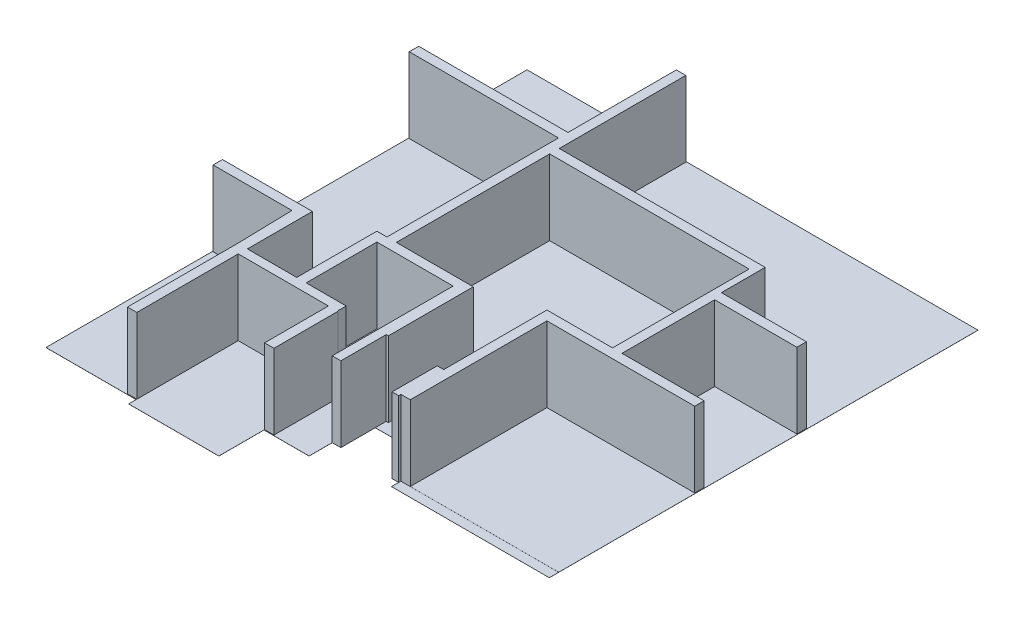
SolidWorks part; units mm, degrees
ref_plane "Front Plane" through (0, 0, 0) normal (0, 0, 1) x (1, 0, 0)
ref_plane "Top Plane" through (0, 0, 0) normal (0, 1, 0) x (1, 0, 0)
ref_plane "Right Plane" through (0, 0, 0) normal (1, 0, 0) x (0, 0, -1)
sketch "Sketch1" plane through (0, 0, 0) normal (0, 1, 0) x (1, 0, 0)
  line L0 (3657.6, 0) -> (3657.6, -304.8)
  line L1 (0, 0) -> (3657.6, 0)
  line L2 (0, 0) -> (0, 19507.2)
  line L3 (0, 19507.2) -> (18288, 19507.2)
  line L4 (18288, 0) -> (18288, 19507.2)
  line L5 (0, 0) -> (18288, 19507.2) construction
  line L6 (0, 19507.2) -> (18288, 0) construction
  line L7 (3657.6, -304.8) -> (7315.2, -304.8)
  line L8 (7315.2, -304.8) -> (7315.2, 0)
  line L9 (7315.2, 0) -> (7315.2, 1524)
  line L10 (7315.2, 1524) -> (9144, 1524)
  line L11 (9144, 1524) -> (9144, 2413)
  line L12 (9144, 2413) -> (11887.2, 2413)
  line L13 (11887.2, 2413) -> (11887.2, 0)
  line L14 (11887.2, 0) -> (18288, 0)
  point P4 (9144, 9753.6)
  dimension "D1" = 18288
  dimension "D2" = 19507.2
  dimension "D3" = 7315.2
  dimension "D4" = 1524
  dimension "D5" = 304.8
  dimension "D6" = 1828.8
  dimension "D7" = 889
  dimension "D8" = 3657.6
  dimension "D9" = 2743.2
  dimension "D10" = 2413
extrude "Boss-Extrude1" add sketch "Sketch1" along normal blind 2.54
sketch "Sketch2" plane through (0, 2.54, 0) normal (0, 1, 0) x (1, 0, 0)
  line L0 (6079.1869, 13964.5874) -> (6079.1869, 19507.2)
  line L11 (18288, 19507.2) -> (0, 19507.2) construction
  line L14 (6079.1869, 13964.5874) -> (14548.139, 13964.5874)
  line L15 (14548.139, 13964.5874) -> (14548.139, 12187.8841)
  line L16 (14548.139, 12187.8841) -> (18288, 12187.8841)
  line L17 (18288, 0) -> (18288, 19507.2) construction
  line L24 (6464.1393, 19507.2) -> (6464.1393, 14349.5397)
  line L25 (6464.1393, 14349.5397) -> (14814.6445, 14349.5397)
  line L26 (14814.6445, 14349.5397) -> (14814.6445, 12572.8365)
  line L27 (14814.6445, 12572.8365) -> (18288, 12572.8365)
  line L28 (6079.1869, 19507.2) -> (6464.1393, 19507.2)
  line L29 (18288, 12572.8365) -> (18288, 12187.8841)
  dimension "D1" = 5542.6126
  dimension "D2" = 5157.6603
  dimension "D3" = 8468.9521
  dimension "D4" = 8350.5052
  dimension "D5" = 1776.7032
  dimension "D6" = 3473.3555
  dimension "D7" = 1776.7032
  dimension "D8" = 3739.861
extrude "Boss-Extrude2" add sketch "Sketch2" along normal blind 3048
sketch "Sketch3" plane through (0, 2.54, 0) normal (0, 1, 0) x (1, 0, 0)
  line L0 (0, 19507.2) -> (0, 0) construction
  line L1 (0, 14704.8804) -> (6079.1869, 14704.8804)
  line L2 (0, 14704.8804) -> (0, 15089.8328)
  line L3 (0, 15089.8328) -> (6079.1869, 15089.8328)
  line L4 (6079.1869, 14704.8804) -> (6079.1869, 15089.8328)
  line L5 (0, 14704.8804) -> (6079.1869, 15089.8328) construction
  line L6 (0, 15089.8328) -> (6079.1869, 14704.8804) construction
  line L7 (6079.1869, 19507.2) -> (6079.1869, 13964.5874) construction
  line L8 (6079.1869, 19507.2) -> (0, 19507.2) construction
  point P4 (3039.5935, 14897.3566)
  dimension "D1" = 384.9524
  dimension "D2" = 4417.3672
extrude "Boss-Extrude3" add sketch "Sketch3" along normal blind 3048
sketch "Sketch4" plane through (0, 2.54, 0) normal (0, 1, 0) x (1, 0, 0)
  line L0 (18288, 0) -> (18288, 12187.8841) construction
  line L1 (11887.2, 2413) -> (11887.2, 0) construction
  line L2 (18288, 2122.5591) -> (11887.2, 2122.5591)
  line L3 (18288, 2122.5591) -> (18288, 2503.5591)
  line L4 (18288, 2503.5591) -> (11887.2, 2503.5591)
  line L5 (11887.2, 2122.5591) -> (11887.2, 2503.5591)
  line L6 (18288, 2122.5591) -> (11887.2, 2503.5591) construction
  line L7 (18288, 2503.5591) -> (11887.2, 2122.5591) construction
  line L8 (11887.2, 0) -> (18288, 0) construction
  point P6 (15087.6, 2313.0591)
  dimension "D1" = 381
  dimension "D2" = 2122.5591
extrude "Boss-Extrude4" add sketch "Sketch4" along normal blind 3048
sketch "Sketch5" plane through (0, 2.54, 0) normal (0, 1, 0) x (1, 0, 0)
  line L1 (9144, 2413) -> (9579.2092, 2413)
  line L2 (9144, 2413) -> (9144, 7747)
  line L3 (9144, 7747) -> (9579.2092, 7747)
  line L4 (9579.2092, 2413) -> (9579.2092, 7747)
  line L5 (9144, 2413) -> (9579.2092, 7747) construction
  line L6 (9144, 7747) -> (9579.2092, 2413) construction
  point P5 (9361.6046, 5080)
  dimension "D1" = 435.2092
  dimension "D2" = 5334
extrude "Boss-Extrude5" add sketch "Sketch5" along normal blind 3048
sketch "Sketch6" plane through (0, 2.54, 0) normal (0, 1, 0) x (1, 0, 0)
  line L0 (18288, 2503.5591) -> (11887.2, 2503.5591) construction
  line L1 (12268.2, 2503.5591) -> (11887.2, 2503.5591)
  line L2 (12268.2, 2503.5591) -> (12268.2, 8426.1696)
  line L3 (12268.2, 8426.1696) -> (11887.2, 8426.1696)
  line L4 (11887.2, 2503.5591) -> (11887.2, 8426.1696)
  line L5 (12268.2, 2503.5591) -> (11887.2, 8426.1696) construction
  line L6 (12268.2, 8426.1696) -> (11887.2, 2503.5591) construction
  line L7 (11887.2, 2122.5591) -> (11887.2, 0) construction
  point P5 (12077.7, 5464.8644)
  dimension "D1" = 381
extrude "Boss-Extrude7" add sketch "Sketch6" along normal blind 3048
sketch "Sketch7" plane through (0, 2.54, 0) normal (0, 1, 0) x (1, 0, 0)
  line L0 (18288, 2503.5591) -> (18288, 12187.8841) construction
  line L1 (12268.2, 8426.1696) -> (18288, 8426.1696)
  line L2 (12268.2, 8426.1696) -> (12268.2, 8045.1696)
  line L3 (12268.2, 8045.1696) -> (18288, 8045.1696)
  line L4 (18288, 8426.1696) -> (18288, 8045.1696)
  line L5 (12268.2, 8426.1696) -> (18288, 8045.1696) construction
  line L6 (12268.2, 8045.1696) -> (18288, 8426.1696) construction
  point P4 (15278.1, 8235.6696)
  dimension "D1" = 381
extrude "Boss-Extrude8" add sketch "Sketch7" along normal blind 3048
sketch "Sketch8" plane through (0, 2.54, 0) normal (0, 1, 0) x (1, 0, 0)
  line L1 (7315.2, 1524) -> (7696.2, 1524)
  line L2 (7315.2, 1524) -> (7315.2, 4137.7312)
  line L3 (7315.2, 4137.7312) -> (7696.2, 4137.7312)
  line L4 (7696.2, 1524) -> (7696.2, 4137.7312)
  line L5 (7315.2, 1524) -> (7696.2, 4137.7312) construction
  line L6 (7315.2, 4137.7312) -> (7696.2, 1524) construction
  point P4 (7505.7, 2830.8656)
  dimension "D1" = 381
extrude "Boss-Extrude9" add sketch "Sketch8" along normal blind 3048
sketch "Sketch9" plane through (0, 2.54, 0) normal (0, 1, 0) x (1, 0, 0)
  line L1 (3657.6, 0) -> (3276.6, 0)
  line L2 (3657.6, 0) -> (3657.6, 4182.505)
  line L3 (3657.6, 4182.505) -> (3276.6, 4182.505)
  line L4 (3276.6, 0) -> (3276.6, 4182.505)
  line L5 (3657.6, 0) -> (3276.6, 4182.505) construction
  line L6 (3657.6, 4182.505) -> (3276.6, 0) construction
  point P4 (3467.1, 2091.2525)
  dimension "D1" = 381
extrude "Boss-Extrude10" add sketch "Sketch9" along normal blind 3048
sketch "Sketch10" plane through (0, 2.54, 0) normal (0, 1, 0) x (1, 0, 0)
  line L0 (7696.2, 4137.7312) -> (7315.2, 4137.7312) construction
  line L1 (7674.1926, 4137.7312) -> (3668.37, 4137.7312)
  line L2 (7674.1926, 4137.7312) -> (7674.1926, 4497.6301)
  line L3 (7674.1926, 4497.6301) -> (3668.37, 4497.6301)
  line L4 (3668.37, 4137.7312) -> (3668.37, 4497.6301)
  line L5 (7674.1926, 4137.7312) -> (3668.37, 4497.6301) construction
  line L6 (7674.1926, 4497.6301) -> (3668.37, 4137.7312) construction
  point P4 (5671.2813, 4317.6806)
extrude "Boss-Extrude11" add sketch "Sketch10" along normal blind 3048
sketch "Sketch11" plane through (0, 2.54, 0) normal (0, 1, 0) x (1, 0, 0)
  line L0 (3276.6, 4182.505) -> (3276.6, 4499.7193)
  line L1 (3276.6, 4182.505) -> (3276.6, 0) construction
  line L2 (3276.6, 4182.505) -> (3276.6, 0) construction
  line L3 (3276.6, 4499.7193) -> (3668.37, 4497.6301)
  line L4 (3668.37, 4497.6301) -> (3668.37, 4137.7312)
  line L5 (3668.37, 4137.7312) -> (3657.6, 4137.7312)
  line L6 (3657.6, 0) -> (3657.6, 4182.505) construction
  line L7 (3657.6, 4137.7312) -> (3657.6, 4182.505)
  line L8 (3657.6, 4182.505) -> (3276.6, 4182.505) construction
  line L9 (3657.6, 4182.505) -> (3276.6, 4182.505) construction
  line L10 (3657.6, 4182.505) -> (3276.6, 4182.505)
extrude "Boss-Extrude12" add sketch "Sketch11" along normal blind 3048
sketch "Sketch13" plane through (0, 2.54, 0) normal (0, 1, 0) x (1, 0, 0)
  line L0 (9144, 7747) -> (5671.2813, 7747)
  line L1 (5671.2813, 7747) -> (5671.2813, 4497.6301)
  line L2 (7674.1926, 4497.6301) -> (3668.37, 4497.6301) construction
  line L3 (5671.2813, 4497.6301) -> (6052.2813, 4497.6301)
  line L4 (7674.1926, 4497.6301) -> (3668.37, 4497.6301) construction
  line L5 (6052.2813, 4497.6301) -> (6052.2813, 7366)
  line L6 (6052.2813, 7366) -> (9144, 7366)
  line L7 (9144, 7747) -> (9144, 2413) construction
  line L8 (9144, 7366) -> (9144, 7747)
  dimension "D1" = 381
  dimension "D2" = 381
extrude "Boss-Extrude13" add sketch "Sketch13" along normal blind 3048
sketch "Sketch14" plane through (0, 2.54, 0) normal (0, 1, 0) x (1, 0, 0)
  line L0 (9579.2092, 7747) -> (5671.2813, 7747) construction
  line L1 (6079.1869, 13964.5874) -> (6460.1869, 13964.5874)
  line L2 (6079.1869, 13964.5874) -> (6079.1869, 7747)
  line L3 (6079.1869, 7747) -> (6460.1869, 7747)
  line L4 (6460.1869, 13964.5874) -> (6460.1869, 7747)
  line L5 (6079.1869, 13964.5874) -> (6460.1869, 7747) construction
  line L6 (6079.1869, 7747) -> (6460.1869, 13964.5874) construction
  point P4 (6269.6869, 10855.7937)
  dimension "D1" = 381
extrude "Boss-Extrude15" add sketch "Sketch14" along normal blind 3048
sketch "Sketch16" plane through (0, 2.54, 0) normal (0, 1, 0) x (1, 0, 0)
  line L1 (11887.2, 0) -> (18288, 0)
  line L2 (11887.2, 0) -> (11887.2, 2122.5591)
  line L3 (11887.2, 2122.5591) -> (18288, 2122.5591)
  line L4 (18288, 0) -> (18288, 2122.5591)
  line L5 (11887.2, 0) -> (18288, 2122.5591) construction
  line L6 (11887.2, 2122.5591) -> (18288, 0) construction
  point P5 (15087.6, 1061.2796)
extrude "Cut-Extrude2" cut sketch "Sketch16" against normal blind 3048
sketch "Sketch18" plane through (0, 2.54, 0) normal (0, 1, 0) x (1, 0, 0)
  line L0 (18288, 8426.1696) -> (11887.2, 8426.1696) construction
  line L1 (14548.139, 12187.8841) -> (14929.139, 12187.8841)
  line L2 (14548.139, 12187.8841) -> (14548.139, 8426.1696)
  line L3 (14548.139, 8426.1696) -> (14929.139, 8426.1696)
  line L4 (14929.139, 12187.8841) -> (14929.139, 8426.1696)
  line L5 (14548.139, 12187.8841) -> (14929.139, 8426.1696) construction
  line L6 (14548.139, 8426.1696) -> (14929.139, 12187.8841) construction
  point P4 (14738.639, 10307.0269)
  dimension "D1" = 381
extrude "Boss-Extrude16" add sketch "Sketch18" along normal blind 3048
sketch "Sketch19" plane through (0, 2.54, 0) normal (0, 1, 0) x (1, 0, 0)
  line L0 (3276.6, 4499.7193) -> (3668.37, 4497.6301)
  line L1 (3668.37, 4497.6301) -> (3276.6, 4499.7193) construction
  line L2 (5671.2813, 4497.6301) -> (3668.37, 4497.6301) construction
  line L3 (3668.37, 4497.6301) -> (3668.37, 7132.8491)
  line L4 (3668.37, 7132.8491) -> (0, 7132.8491)
  line L5 (0, 14704.8804) -> (0, 0) construction
  line L6 (0, 7132.8491) -> (0, 6751.8491)
  line L7 (0, 6751.8491) -> (3221.6739, 6751.8491)
  line L8 (3221.6739, 6751.8491) -> (3276.6, 4499.7193)
  dimension "D1" = 381
extrude "Boss-Extrude17" add sketch "Sketch19" along normal blind 3048
sketch "Sketch20" plane through (0, 0, 0) normal (0, 0, 1) x (1, 0, 0)
  line L1 (3276.6, 3050.54) -> (3657.6, 3050.54)
  line L2 (3276.6, 3050.54) -> (3276.6, 2.54)
  line L3 (3276.6, 2.54) -> (3657.6, 2.54)
  line L4 (3657.6, 3050.54) -> (3657.6, 2.54)
  line L5 (3276.6, 3050.54) -> (3657.6, 2.54) construction
  line L6 (3276.6, 2.54) -> (3657.6, 3050.54) construction
  point P4 (3467.1, 1526.54)
extrude "Cut-Extrude3" cut sketch "Sketch20" against normal blind 25.4
sketch "Sketch21" plane through (0, 0, -1524) normal (0, 0, 1) x (1, 0, 0)
  line L1 (7696.2, 2.54) -> (7315.2, 2.54)
  line L2 (7696.2, 2.54) -> (7696.2, 3050.54)
  line L3 (7696.2, 3050.54) -> (7315.2, 3050.54)
  line L4 (7315.2, 2.54) -> (7315.2, 3050.54)
  line L5 (7696.2, 2.54) -> (7315.2, 3050.54) construction
  line L6 (7696.2, 3050.54) -> (7315.2, 2.54) construction
  point P4 (7505.7, 1526.54)
extrude "Cut-Extrude4" cut sketch "Sketch21" against normal blind 25.4
sketch "Sketch22" plane through (0, 0, -2413) normal (0, 0, 1) x (1, 0, 0)
  line L1 (9579.2092, 2.54) -> (11887.2, 2.54)
  line L2 (9579.2092, 2.54) -> (9579.2092, 3050.54)
  line L3 (9579.2092, 3050.54) -> (11887.2, 3050.54)
  line L4 (11887.2, 2.54) -> (11887.2, 3050.54)
  line L5 (9579.2092, 2.54) -> (11887.2, 3050.54) construction
  line L6 (9579.2092, 3050.54) -> (11887.2, 2.54) construction
  point P4 (10733.2046, 1526.54)
extrude "Boss-Extrude18" add sketch "Sketch22" against normal blind 1828.8
sketch "Sketch23" plane through (0, 0, -2413) normal (0, 0, 1) x (1, 0, 0)
  line L0 (9144, 0) -> (11887.2, 0) construction
  line L1 (9492.1389, 0) -> (11624.0435, 0)
  line L2 (9492.1389, 0) -> (9492.1389, 3050.54)
  line L3 (9492.1389, 3050.54) -> (11624.0435, 3050.54)
  line L4 (11624.0435, 0) -> (11624.0435, 3050.54)
  line L5 (9492.1389, 0) -> (11624.0435, 3050.54) construction
  line L6 (9492.1389, 3050.54) -> (11624.0435, 0) construction
  line L7 (9144, 3050.54) -> (11887.2, 3050.54) construction
  point P4 (10558.0912, 1525.27)
extrude "Cut-Extrude5" cut sketch "Sketch23" against normal blind 1447.8
sketch "Sketch24" plane through (0, 0, -2413) normal (0, 0, 1) x (1, 0, 0)
  line L1 (9492.1389, 0) -> (9144, 0)
  line L2 (9492.1389, 0) -> (9492.1389, 3050.54)
  line L3 (9492.1389, 3050.54) -> (9144, 3050.54)
  line L4 (9144, 0) -> (9144, 3050.54)
  line L5 (9492.1389, 0) -> (9144, 3050.54) construction
  line L6 (9492.1389, 3050.54) -> (9144, 0) construction
  point P4 (9318.0694, 1525.27)
extrude "Cut-Extrude6" cut sketch "Sketch24" against normal blind 50.8
sketch "Sketch26" plane through (0, 0, -3860.8) normal (0, 0, 1) x (1, 0, 0)
  line L0 (9492.1389, 3050.54) -> (9492.1389, 0) construction
  line L1 (11624.0435, 3050.54) -> (9492.1389, 3050.54)
  line L2 (11624.0435, 3050.54) -> (11624.0435, 2.54)
  line L3 (11624.0435, 2.54) -> (9492.1389, 2.54)
  line L4 (9492.1389, 3050.54) -> (9492.1389, 2.54)
  line L5 (11624.0435, 3050.54) -> (9492.1389, 2.54) construction
  line L6 (11624.0435, 2.54) -> (9492.1389, 3050.54) construction
  line L7 (9492.1389, 0) -> (11624.0435, 0) construction
  point P4 (10558.0912, 1526.54)
  dimension "D1" = 2.54
extrude "Cut-Extrude7" cut sketch "Sketch26" against normal blind 441.706
sketch "Sketch28" plane through (0, 0, -2122.5591) normal (0, 0, 1) x (1, 0, 0)
  line L0 (18288, 3050.54) -> (18288, 0) construction
  line L1 (11887.2, 3050.54) -> (18288, 3050.54)
  line L2 (11887.2, 3050.54) -> (11887.2, 0.254)
  line L3 (11887.2, 0.254) -> (18288, 0.254)
  line L4 (18288, 3050.54) -> (18288, 0.254)
  line L5 (11887.2, 3050.54) -> (18288, 0.254) construction
  line L6 (11887.2, 0.254) -> (18288, 3050.54) construction
  line L7 (11887.2, 0) -> (18288, 0) construction
  point P4 (15087.6, 1525.397)
  dimension "D1" = 0.254
extrude "Cut-Extrude9" cut sketch "Sketch28" against normal blind 381
sketch "Sketch29" plane through (0, 0, 0) normal (-1, 0, 0) x (0, 0, 1)
  line L0 (-14704.8804, 3050.54) -> (-14704.8804, 2.54) construction
  line L1 (-15089.8328, 3050.54) -> (-14704.8804, 3050.54)
  line L2 (-15089.8328, 3050.54) -> (-15089.8328, 0.254)
  line L3 (-15089.8328, 0.254) -> (-14704.8804, 0.254)
  line L4 (-14704.8804, 3050.54) -> (-14704.8804, 0.254)
  line L5 (-15089.8328, 3050.54) -> (-14704.8804, 0.254) construction
  line L6 (-15089.8328, 0.254) -> (-14704.8804, 3050.54) construction
  line L7 (-19507.2, 0) -> (0, 0) construction
  point P4 (-14897.3566, 1525.397)
  dimension "D1" = 0.254
extrude "Cut-Extrude10" cut sketch "Sketch29" against normal blind 25.4
sketch "Sketch30" plane through (0, 0, 0) normal (-1, 0, 0) x (0, 0, 1)
  line L0 (-6751.8491, 3050.54) -> (-6751.8491, 2.54) construction
  line L1 (-7132.8491, 3050.54) -> (-6751.8491, 3050.54)
  line L2 (-7132.8491, 3050.54) -> (-7132.8491, 0.254)
  line L3 (-7132.8491, 0.254) -> (-6751.8491, 0.254)
  line L4 (-6751.8491, 3050.54) -> (-6751.8491, 0.254)
  line L5 (-7132.8491, 3050.54) -> (-6751.8491, 0.254) construction
  line L6 (-7132.8491, 0.254) -> (-6751.8491, 3050.54) construction
  line L7 (-19507.2, 0) -> (0, 0) construction
  point P4 (-6942.3491, 1525.397)
  dimension "D1" = 0.254
extrude "Cut-Extrude11" cut sketch "Sketch30" against normal blind 25.4
sketch "Sketch31" plane through (18288, 0, 0) normal (1, 0, 0) x (0, 0, -1)
  line L0 (8426.1696, 3050.54) -> (8426.1696, 2.54) construction
  line L1 (8045.1696, 3050.54) -> (8426.1696, 3050.54)
  line L2 (8045.1696, 3050.54) -> (8045.1696, 0.254)
  line L3 (8045.1696, 0.254) -> (8426.1696, 0.254)
  line L4 (8426.1696, 3050.54) -> (8426.1696, 0.254)
  line L5 (8045.1696, 3050.54) -> (8426.1696, 0.254) construction
  line L6 (8045.1696, 0.254) -> (8426.1696, 3050.54) construction
  line L7 (2122.5591, 0) -> (19507.2, 0) construction
  point P4 (8235.6696, 1525.397)
  dimension "D1" = 0.254
extrude "Cut-Extrude12" cut sketch "Sketch31" against normal blind 25.4
sketch "Sketch32" plane through (18288, 0, 0) normal (1, 0, 0) x (0, 0, -1)
  line L0 (12572.8365, 3050.54) -> (12572.8365, 2.54) construction
  line L1 (12187.8841, 3050.54) -> (12572.8365, 3050.54)
  line L2 (12187.8841, 3050.54) -> (12187.8841, 0.254)
  line L3 (12187.8841, 0.254) -> (12572.8365, 0.254)
  line L4 (12572.8365, 3050.54) -> (12572.8365, 0.254)
  line L5 (12187.8841, 3050.54) -> (12572.8365, 0.254) construction
  line L6 (12187.8841, 0.254) -> (12572.8365, 3050.54) construction
  line L7 (2122.5591, 0) -> (19507.2, 0) construction
  point P4 (12380.3603, 1525.397)
  dimension "D1" = 0.254
extrude "Cut-Extrude13" cut sketch "Sketch32" against normal blind 25.4
sketch "Sketch33" plane through (0, 0, -19507.2) normal (0, 0, -1) x (-1, 0, 0)
  line L0 (-6079.1869, 3050.54) -> (-6079.1869, 2.54) construction
  line L1 (-6464.1393, 3050.54) -> (-6079.1869, 3050.54)
  line L2 (-6464.1393, 3050.54) -> (-6464.1393, 0.254)
  line L3 (-6464.1393, 0.254) -> (-6079.1869, 0.254)
  line L4 (-6079.1869, 3050.54) -> (-6079.1869, 0.254)
  line L5 (-6464.1393, 3050.54) -> (-6079.1869, 0.254) construction
  line L6 (-6464.1393, 0.254) -> (-6079.1869, 3050.54) construction
  line L7 (-18288, 0) -> (0, 0) construction
  point P4 (-6271.6631, 1525.397)
  dimension "D1" = 0.254
extrude "Cut-Extrude14" cut sketch "Sketch33" against normal blind 25.4
